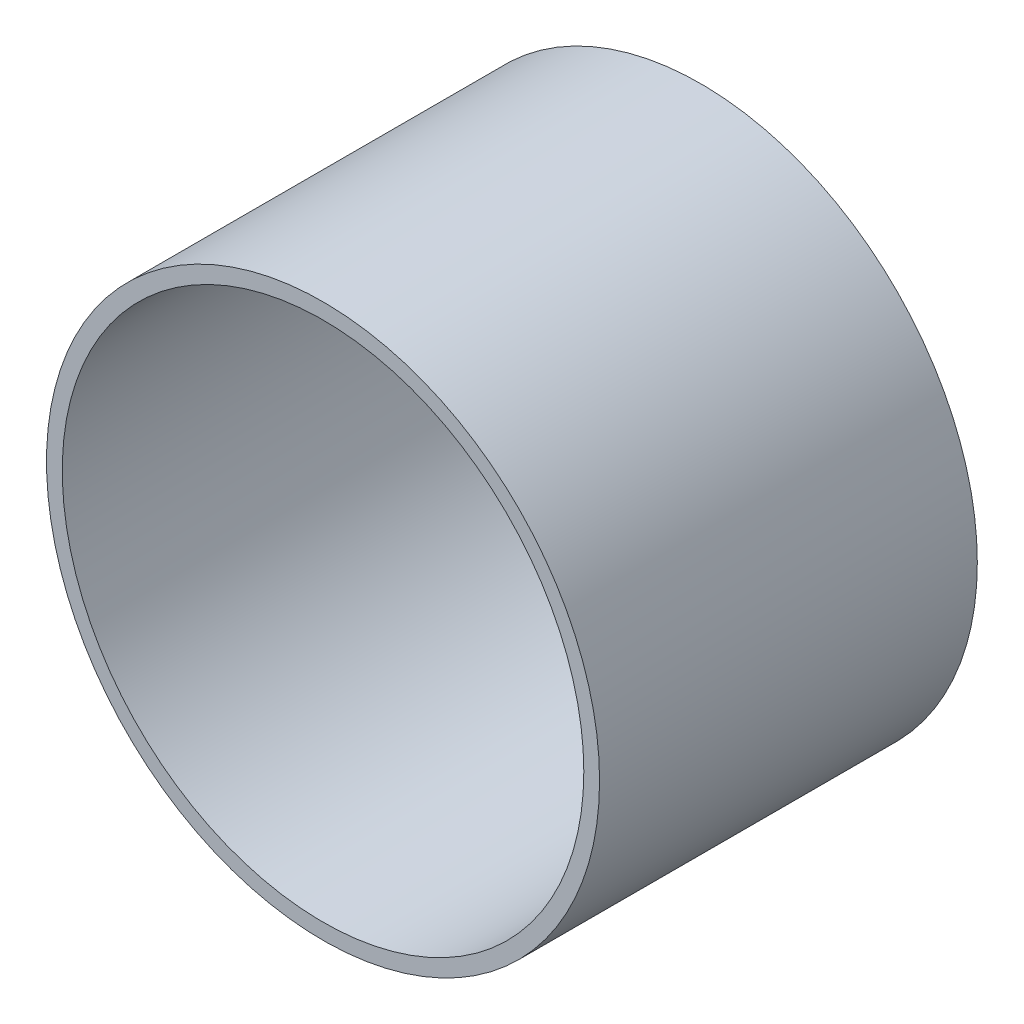
SolidWorks part; units mm, degrees
ref_plane "Front Plane" through (0, 0, 0) normal (0, 0, 1) x (1, 0, 0)
ref_plane "Top Plane" through (0, 0, 0) normal (0, 1, 0) x (1, 0, 0)
ref_plane "Right Plane" through (0, 0, 0) normal (1, 0, 0) x (0, 0, -1)
sketch "Sketch1" plane through (0, 0, 0) normal (0, 0, 1) x (1, 0, 0)
  circle A0 centre (0, 0) radius 50
  circle A1 centre (0, 0) radius 47.15
  dimension "D1" = 100
  dimension "D2" = 94.3
extrude "Boss-Extrude1" add sketch "Sketch1" along normal blind 68.3
